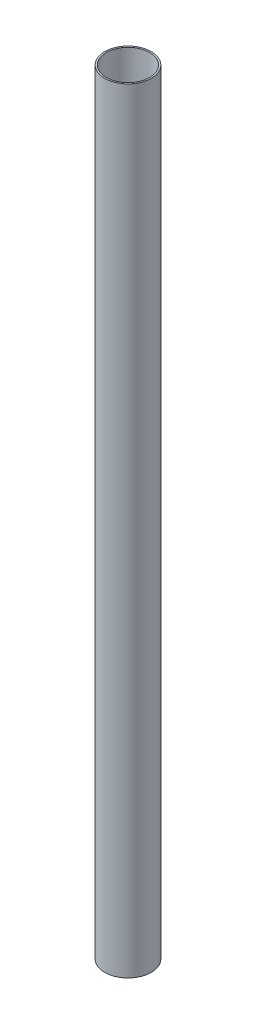
SolidWorks part; units mm, degrees
material "铜"
ref_plane "前视基准面" through (0, 0, 0) normal (0, 0, 1) x (1, 0, 0)
ref_plane "上视基准面" through (0, 0, 0) normal (0, 1, 0) x (1, 0, 0)
ref_plane "右视基准面" through (0, 0, 0) normal (1, 0, 0) x (0, 0, -1)
sketch "草图1" plane through (0, 0, 0) normal (0, 1, 0) x (1, 0, 0)
  circle A0 centre (0, 0) radius 3
  circle A1 centre (0, 0) radius 2.8
  dimension "D1" = 6
  dimension "D2" = 0.2
extrude "凸台-拉伸1" add sketch "草图1" along normal blind 100
